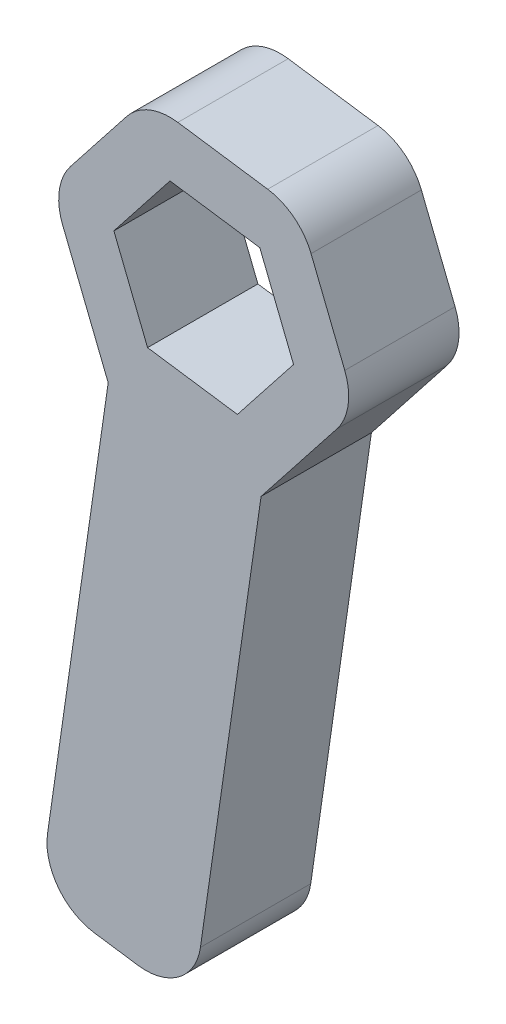
SolidWorks part; units mm, degrees
other "Markup1"
sketch "Sketch2" plane through (5.2573, -22.174, 4) normal (0.6264, -0.3817, 0.6797) x (0.7214, -0.0465, -0.6909)
ref_plane "Front Plane" through (0, 0, 0) normal (0, 0, 1) x (1, 0, 0)
ref_plane "Top Plane" through (0, 0, 0) normal (0, 1, 0) x (1, 0, 0)
ref_plane "Right Plane" through (0, 0, 0) normal (1, 0, 0) x (0, 0, -1)
sketch "Sketch1" plane through (0, 0, 0) normal (0, 0, 1) x (1, 0, 0)
  line L0 (2.0799, -5.1997) -> (4.829, -1.7061)
  line L1 (1.2222, -3.0555) -> (3.2573, -0.4693)
  line L2 (3.2573, -0.4693) -> (2.0351, 2.5862)
  line L3 (2.0351, 2.5862) -> (-1.2222, 3.0555)
  line L4 (-1.2222, 3.0555) -> (-3.2573, 0.4693)
  line L5 (-3.2573, 0.4693) -> (-2.0351, -2.5862)
  line L6 (-2.0351, -2.5862) -> (1.2222, -3.0555)
  line L7 (5.1142, 0.2735) -> (3.892, 3.329)
  line L8 (2.3203, 4.5658) -> (-0.937, 5.0351)
  line L9 (-2.794, 4.2923) -> (-4.829, 1.7061)
  line L10 (-5.1142, -0.2735) -> (-3.4632, -4.4011)
  line L11 (-3.4632, -4.4011) -> (2.0799, -5.1997)
  line L12 (-3.4632, -4.4011) -> (2.0799, -5.1997)
  line L13 (-3.4632, -4.4011) -> (-5.6617, -19.6606)
  line L14 (2.0799, -5.1997) -> (-0.1186, -20.4592)
  line L15 (-3.9674, -21.9254) -> (-2.3834, -22.1536)
  line L16 (2.0799, -5.1997) -> (5.5431, -0.7986) construction
  line L17 (5.5431, -0.7986) -> (3.4632, 4.4011) construction
  line L18 (3.4632, 4.4011) -> (-2.0799, 5.1997) construction
  line L19 (-2.0799, 5.1997) -> (-5.5431, 0.7986) construction
  line L20 (-5.5431, 0.7986) -> (-3.4632, -4.4011) construction
  circle A0 centre (0, 0) radius 2.85 construction
  arc A1 (-0.1186, -20.4592) -> (-2.3834, -22.1536) centre (-2.0982, -20.174) cw
  arc A2 (-3.9674, -21.9254) -> (-5.6617, -19.6606) centre (-3.6821, -19.9458) cw
  arc A3 (4.829, -1.7061) -> (5.1142, 0.2735) centre (3.2573, -0.4693) ccw
  arc A4 (3.892, 3.329) -> (2.3203, 4.5658) centre (2.0351, 2.5862) ccw
  arc A5 (-0.937, 5.0351) -> (-2.794, 4.2923) centre (-1.2222, 3.0555) ccw
  arc A6 (-5.1142, -0.2735) -> (-4.829, 1.7061) centre (-3.2573, 0.4693) cw
  point P1 (-0.4064, -2.8209)
  dimension "D3" = 2
  dimension "D1" = 5.7
  dimension "D2" = 2
extrude "Boss-Extrude1" add sketch "Sketch1" along normal blind 4 contours A6 L10 L11 L0 A3 L7 A4 L8 A5 L9 L6 L5 L4 L3 L2 L1 | A2 L15 A1 L14 L11 L13
